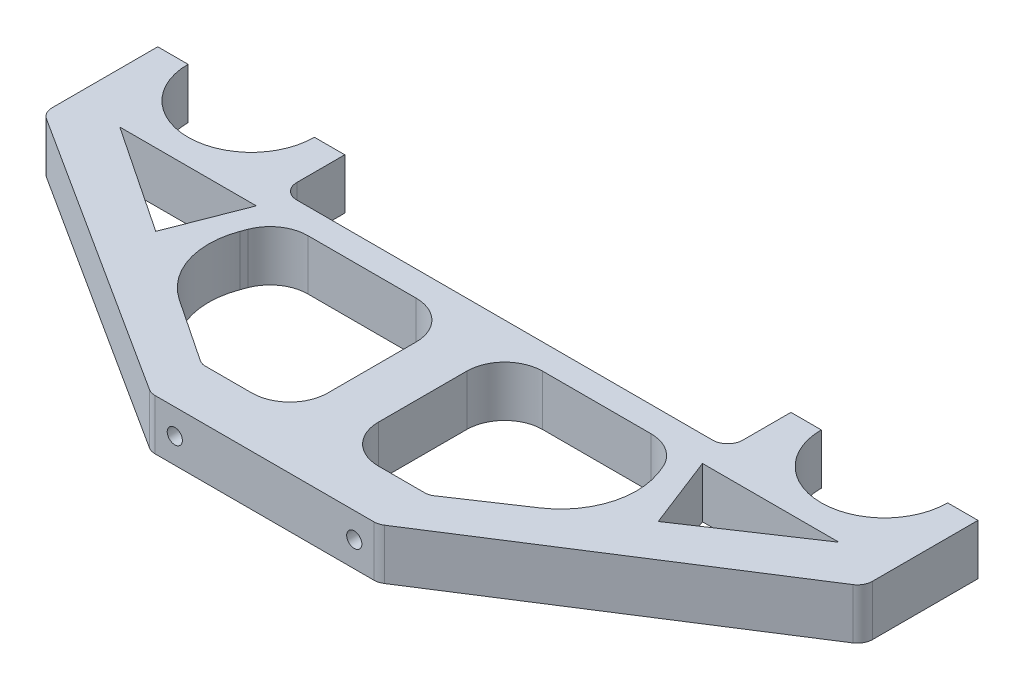
SolidWorks part; units mm, degrees
ref_plane "Front Plane" through (0, 0, 0) normal (0, 0, 1) x (1, 0, 0)
ref_plane "Top Plane" through (0, 0, 0) normal (0, 1, 0) x (1, 0, 0)
ref_plane "Right Plane" through (0, 0, 0) normal (1, 0, 0) x (0, 0, -1)
sketch "Sketch1" plane through (0, 0, 0) normal (0, 1, 0) x (1, 0, 0)
  line L0 (0, 0) -> (62.625, 0)
  line L1 (75.125, 0) -> (81.125, 0)
  line L2 (62.625, 12.5) -> (62.625, 17.5)
  line L3 (112.5, 0) -> (106.5, 0)
  line L4 (106.5, 0) -> (106.5, 17.5)
  line L5 (106.5, 17.5) -> (62.625, 17.5)
  line L6 (81.125, 0) -> (81.125, 17.5)
  line L7 (81.125, 17.5) -> (62.625, 17.5)
  line L8 (44.125, -17.5) -> (44.125, 17.5)
  line L10 (44.125, 17.5) -> (81.125, 17.5)
  line L11 (81.125, -17.5) -> (81.125, 17.5)
  line L12 (44.125, -17.5) -> (81.125, 17.5) construction
  line L13 (44.125, 17.5) -> (81.125, -17.5) construction
  line L14 (44.125, -17.5) -> (5, -17.5)
  line L15 (5, -17.5) -> (0, -17.5)
  line L16 (0, -17.5) -> (0, -12.5)
  line L17 (0, -12.5) -> (5, -12.5)
  line L18 (5, -12.5) -> (44.125, -12.5)
  line L19 (5, -12.5) -> (5, -17.5)
  line L20 (5, -17.5) -> (5, -55)
  line L21 (0, -55) -> (10, -55)
  line L22 (5, -55) -> (0, -55)
  line L23 (5, -55) -> (5, -17.5)
  line L24 (5, -17.5) -> (0, -17.5)
  line L25 (0, -55) -> (0, -17.5)
  line L26 (10, -55) -> (15, -55)
  line L27 (81.125, -17.5) -> (71.125, -17.5)
  line L28 (71.125, -17.5) -> (15, -55)
  line L29 (15, -55) -> (22.5, -55)
  line L30 (81.125, -17.5) -> (81.125, -22.5)
  line L31 (71.125, -17.5) -> (44.125, -17.5)
  line L32 (22.5, -55) -> (22.5, -60)
  line L33 (22.5, -60) -> (81.125, -22.5)
  line L34 (22.5, -60) -> (0, -60)
  line L35 (0, -60) -> (0, -55)
  line L36 (24.5625, -17.5) -> (48.25, -17.5)
  line L37 (24.5625, -17.5) -> (63.25, -17.5)
  line L38 (38.0567, -39.5946) -> (49.6962, -31.8177)
  line L39 (71.125, -17.5) -> (5, -55)
  line L40 (49.6962, -31.8177) -> (44.125, -17.5)
  line L41 (39.125, -17.5) -> (45.5388, -34.5954)
  line L42 (15, -55) -> (15, -50)
  line L43 (15, -50) -> (22.4833, -50)
  line L44 (15, -50) -> (5, -50)
  circle A0 centre (62.625, 0) radius 12.5
  circle A1 centre (44.125, -17.5) radius 5
  circle A2 centre (49.6962, -31.8177) radius 5
  point P9 (62.625, 17.5)
  point P13 (93.8125, 0)
  dimension "D2" = 25
  dimension "D18" = 10
  dimension "D19" = 10
  dimension "D1" = 62.625
  dimension "D3" = 6
  dimension "D4" = 5
  dimension "D6" = 39.125
  dimension "D7" = 5
  dimension "D8" = 5
  dimension "D9" = 5
  dimension "D10" = 37.5
  dimension "D11" = 10
  dimension "D12" = 5
  dimension "D13" = 7.5
  dimension "D14" = 10
  dimension "D15" = 27
  dimension "D16" = 5
  dimension "D17" = 5
  dimension "D20" = 5
  dimension "D5" = 2
extrude "Boss-Extrude1" add sketch "Sketch1" along normal blind 10 contours A1 L31 L27 L11 L1 A0 L0 L8 | A2 L38 L28 L29 L32 L33 L30 L27 | L28 A2 | L39 L41 L28 L40 | L40 A2 L41 L39 | A2 L40 A1 L41 | L41 A1 L40 L14 | L37 A1 L8 L31 | L8 A1 L14 | A1 L18 L19 L14 L37 | L19 L17 L16 L15 | L35 L34 L32 L29 L26 L21 | L39 L44 L23 | L42 L44 L39 L21 L26 | L43 L42 L28
mirror "Mirror1" about plane through (0, 10, 0) normal (-1, 0, 0) of "Boss-Extrude1"
ref_plane "Plane1" through (0, 0, 0) normal (1, 0, 0) x (0, 0, -1)
sketch "Sketch9" plane through (0, 0, 60) normal (0, 0, 1) x (1, 0, 0)
  line L0 (0, 0) -> (0, 10)
  line L1 (22.5, 0) -> (-22.5, 0) construction
  line L2 (22.5, 10) -> (-22.5, 10) construction
  line L3 (0, 5) -> (-17.75, 5)
  line L4 (-17.75, 5) -> (-35.75, 5)
  circle A0 centre (-17.75, 5) radius 1.5
  circle A1 centre (-35.75, 5) radius 1.5
  dimension "D2" = 3
  dimension "D4" = 3
  dimension "D1" = 17.75
  dimension "D3" = 18
extrude "Cut-Extrude5" cut sketch "Sketch9" against normal up to next contours A0
mirror "Mirror2" about plane through (0, 0, 0) normal (1, 0, 0) of "Cut-Extrude5"
fillet "Fillet13" radius 7.5 1 edges at (39.125, 5, 17.5)
fillet "Fillet14" radius 15 1 edges at (45.5388, 5, 34.5954)
fillet "Fillet16" radius 7.5 1 edges at (5, 5, 17.5)
fillet "Fillet18" radius 7.5 1 edges at (-5, 5, 17.5)
fillet "Fillet19" radius 7.5 1 edges at (-39.125, 5, 17.5)
fillet "Fillet22" radius 3 1 edges at (44.125, 5, 12.5)
fillet "Fillet23" radius 3 1 edges at (-44.125, 5, 12.5)
fillet "Fillet24" radius 15 1 edges at (-45.5388, 5, 34.5954)
fillet "Fillet28" radius 3 1 edges at (22.5, 5, 60)
fillet "Fillet29" radius 3 1 edges at (-22.5, 5, 60)
fillet "Fillet30" radius 3 1 edges at (81.125, 5, 22.5)
fillet "Fillet31" radius 3 1 edges at (-81.125, 5, 22.5)
fillet "Fillet32" radius 7.5 1 edges at (-5, 5, 50)
fillet "Fillet34" radius 7.5 1 edges at (5, 5, 50)
fillet "Fillet35" radius 2.5 1 edges at (-22.4833, 5, 50)
fillet "Fillet36" radius 2.5 1 edges at (22.4833, 5, 50)
